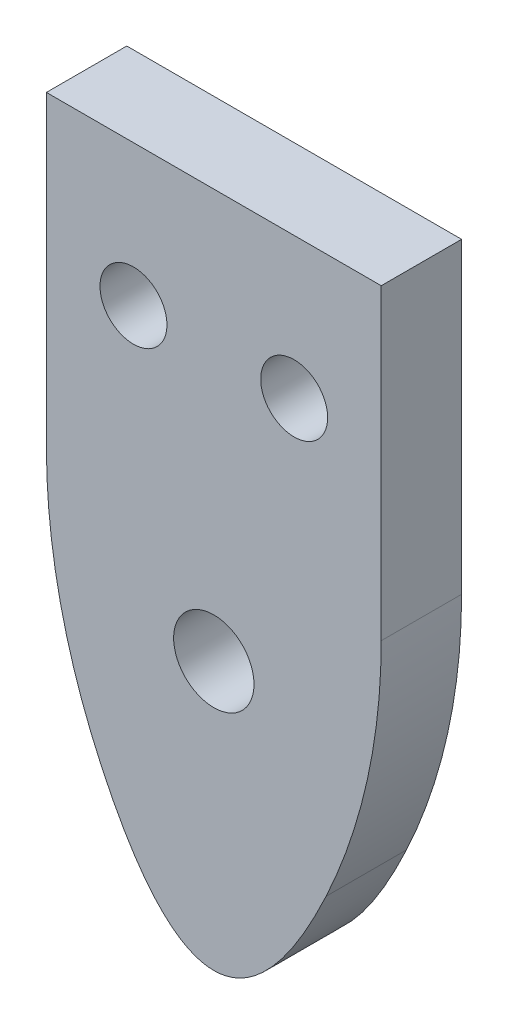
SolidWorks part; units mm, degrees
ref_plane "Plan de face" through (0, 0, 0) normal (0, 0, 1) x (1, 0, 0)
ref_plane "Plan de dessus" through (0, 0, 0) normal (0, 1, 0) x (1, 0, 0)
ref_plane "Plan de droite" through (0, 0, 0) normal (1, 0, 0) x (0, 0, -1)
sketch "Esquisse1" plane through (0, 0, 0) normal (0, 0, 1) x (1, 0, 0)
  line L0 (-0.7304, -0.3) -> (9.2087, -0.3) construction
  line L1 (-4.9778, -4.0848) -> (1.0222, -4.0848)
  line L2 (-4.9778, -4.0848) -> (-4.9778, -1.5805)
  line L3 (-4.9778, -1.5805) -> (1.0222, -1.5805)
  line L4 (1.0222, -4.0848) -> (1.0222, -1.5805)
  line L5 (-4.9778, -4.0848) -> (1.0222, -1.5805) construction
  line L6 (-4.9778, -1.5805) -> (1.0222, -4.0848) construction
  line L7 (-1.9778, -17.0085) -> (-1.9778, 2.9915) construction
  line L8 (-8.2278, -22.8326) -> (4.2722, -22.8326) construction
  line L9 (-8.2278, -22.8326) -> (-8.2278, 17.1674) construction
  line L10 (-8.2278, 17.1674) -> (4.2722, 17.1674) construction
  line L11 (4.2722, -22.8326) -> (4.2722, 17.1674) construction
  line L12 (-8.2278, -22.8326) -> (4.2722, 17.1674) construction
  line L13 (-8.2278, 17.1674) -> (4.2722, -22.8326) construction
  line L14 (-1.6747, -12.8326) -> (-14.3363, -12.8326) construction
  line L15 (-8.2278, 2.4341) -> (4.2722, 2.4341)
  line L16 (-8.2278, 2.4341) -> (-8.2278, -12.8326)
  line L17 (4.2722, -12.8326) -> (4.2722, 2.4341)
  circle A0 centre (-4.9778, -2.8326) radius 1.25
  circle A1 centre (1.0222, -2.8326) radius 1.25
  circle A2 centre (-1.9778, -12.8326) radius 1.5
  spline S0 degree 2 poles (-8.2278, -12.8326) (-1.9778, -32.8326) (4.2722, -12.8326) knots 0 0 0 1 1 1
  point P0 (-1.9778, -2.8326)
  point P11 (-1.9778, -2.8326)
  point P16 (-1.9778, -22.8326)
  point P18 (-1.9778, -12.8326)
  point P21 (-8.2278, -12.8326)
  point P23 (4.2722, -12.8326)
  dimension "D2" = 2.5
  dimension "D3" = 12.5
  dimension "D6" = 3
  dimension "D1" = 3
  dimension "D4" = 20
  dimension "D5" = 10
extrude "Boss.-Extru.1" add sketch "Esquisse1" along normal blind 3 contours L16 S0 L17 L15 A1 L4 L1 L2 A0 L3 A2 | A1 L4 L3 L2 A0 L1
fillet "Congé3" radius 22 1 edges at (4.2722, -12.8326, 1.5)
fillet "Congé4" radius 22 3 edges at (-8.2278, -12.8326, 1.5)
